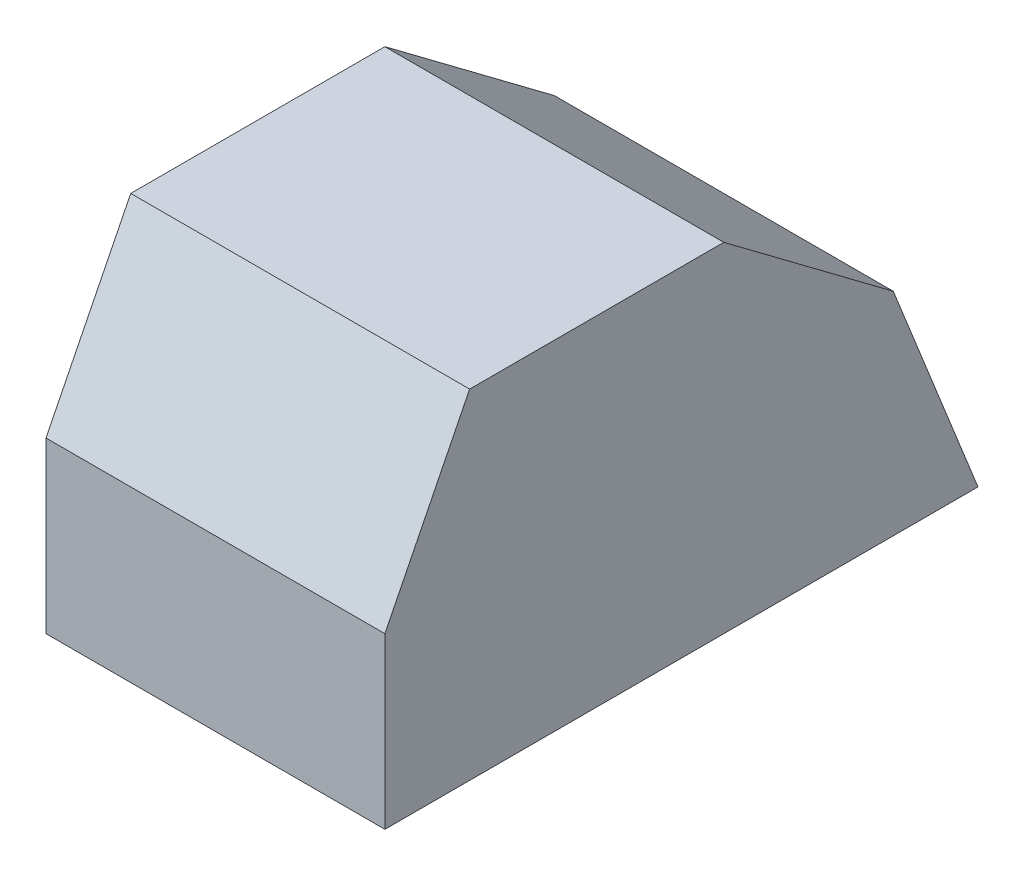
SolidWorks part; units mm, degrees
ref_plane "Front Plane" through (0, 0, 0) normal (0, 0, 1) x (1, 0, 0)
ref_plane "Top Plane" through (0, 0, 0) normal (0, 1, 0) x (1, 0, 0)
ref_plane "Right Plane" through (0, 0, 0) normal (1, 0, 0) x (0, 0, -1)
sketch "Sketch1" plane through (0, 0, 0) normal (1, 0, 0) x (0, 0, -1)
  line L0 (0, 0) -> (70, 0)
  line L1 (70, 0) -> (60, 25)
  line L2 (60, 25) -> (40, 40)
  line L3 (40, 40) -> (10, 40)
  line L4 (10, 40) -> (0, 20)
  line L5 (0, 20) -> (0, 0)
extrude "Boss-Extrude1" add sketch "Sketch1" along normal blind 40
